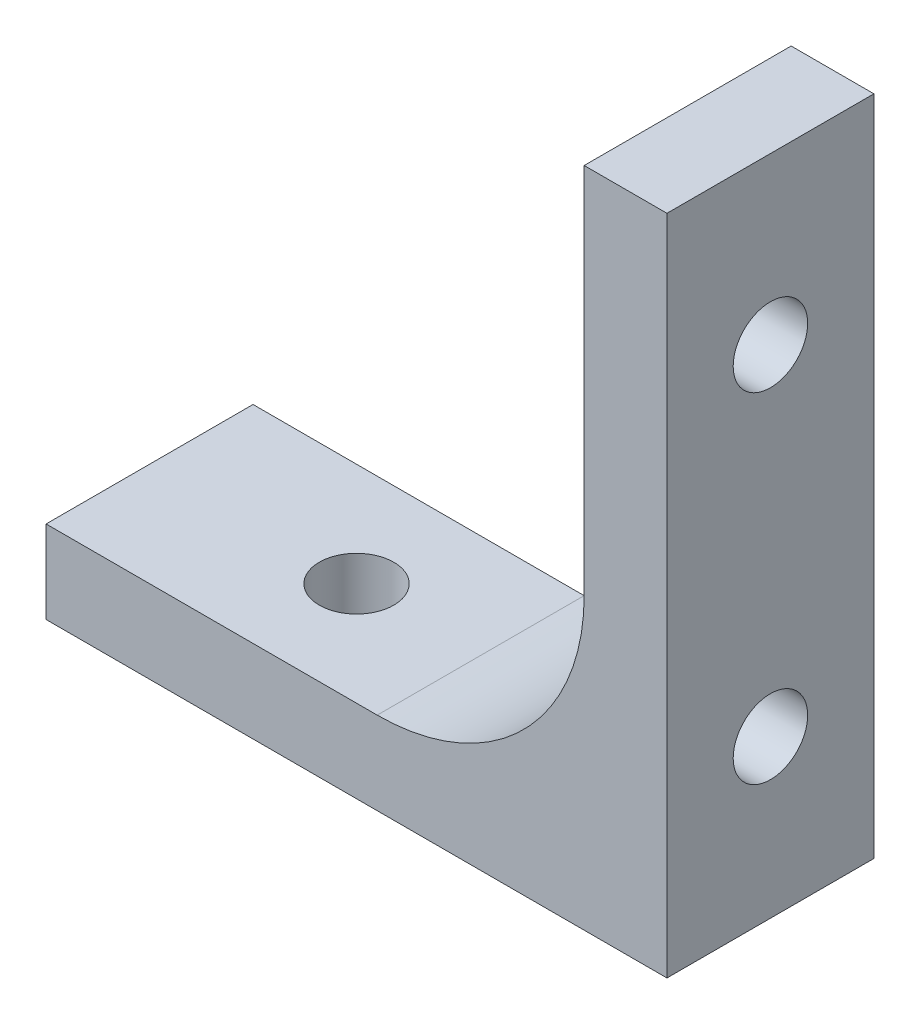
SolidWorks part; units mm, degrees
ref_plane "Front Plane" through (0, 0, 0) normal (0, 0, 1) x (1, 0, 0)
ref_plane "Top Plane" through (0, 0, 0) normal (0, 1, 0) x (1, 0, 0)
ref_plane "Right Plane" through (0, 0, 0) normal (1, 0, 0) x (0, 0, -1)
sketch "Sketch2" plane through (0, 0, 0) normal (0, 1, 0) x (1, 0, 0)
  line L1 (0, 0) -> (19.05, 0)
  line L2 (0, 0) -> (0, 6.35)
  line L3 (0, 6.35) -> (19.05, 6.35)
  line L4 (19.05, 0) -> (19.05, 6.35)
  dimension "D1" = 6.35
  dimension "D2" = 19.05
extrude "Boss-Extrude1" add sketch "Sketch2" along normal blind 2.54
sketch "Sketch3" plane through (0, 2.54, 0) normal (0, 1, 0) x (1, 0, 0)
  line L0 (0, 0) -> (19.05, 0) construction
  line L1 (19.05, 6.35) -> (16.51, 6.35)
  line L2 (19.05, 6.35) -> (19.05, 0)
  line L3 (19.05, 0) -> (16.51, 0)
  line L4 (16.51, 6.35) -> (16.51, 0)
  dimension "D1" = 2.54
extrude "Boss-Extrude2" add sketch "Sketch3" along normal blind 17.78
fillet "Fillet1" radius 6.35 1 edges
sketch "Sketch4" plane through (0, 2.54, 0) normal (0, 1, 0) x (1, 0, 0)
  line L0 (-33.1607, 3.175) -> (25.5475, 3.175) construction
  line L2 (19.05, 0) -> (19.05, 6.35) construction
  circle A0 centre (6.35, 3.175) radius 1.143
  point P3 (-3.8066, 3.175)
  dimension "D1" = 2.286
  dimension "D2" = 12.7
extrude "Cut-Extrude1" cut sketch "Sketch4" against normal through all
sketch "Sketch5" plane through (16.51, 0, 0) normal (-1, 0, 0) x (0, 0, 1)
  line L0 (-3.175, 15.6443) -> (-3.175, -11.5011) construction
  line L2 (0, 0) -> (-6.35, 0) construction
  circle A0 centre (-3.175, 15.24) radius 1.143
  circle A1 centre (-3.175, 4.826) radius 1.143
  dimension "D1" = 2.286
  dimension "D2" = 10.414
  dimension "D3" = 4.826
extrude "Cut-Extrude2" cut sketch "Sketch5" against normal through all both and the other way through all
